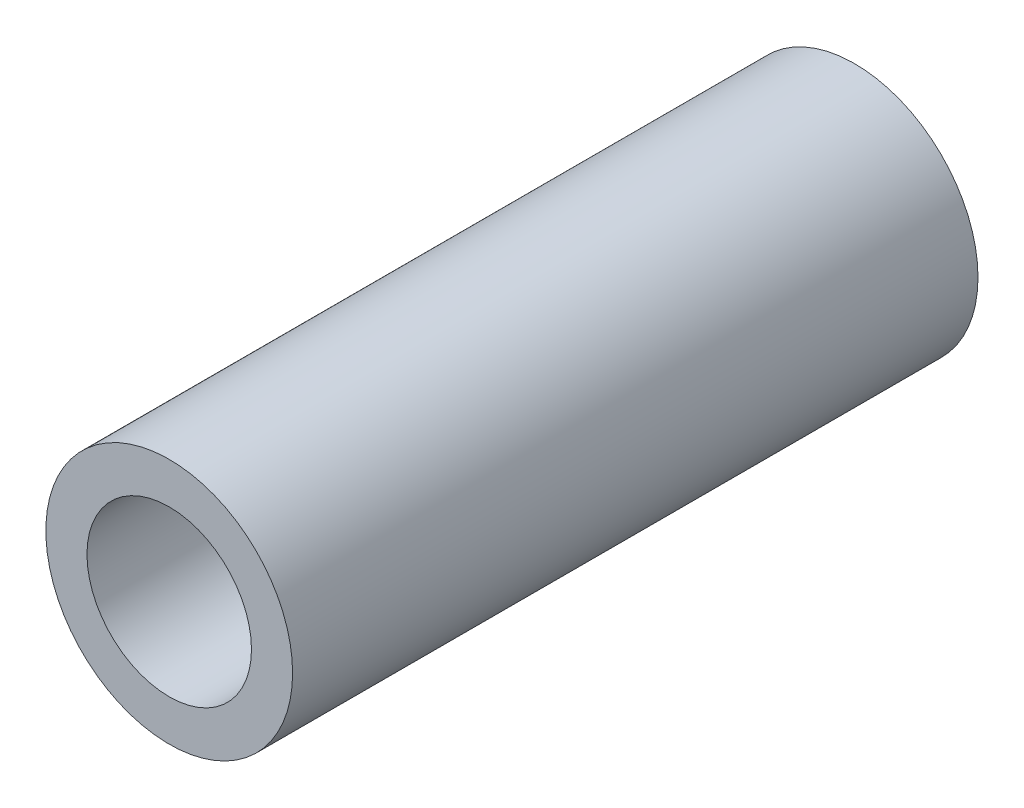
SolidWorks part; units mm, degrees
ref_plane "前视基准面" through (0, 0, 0) normal (0, 0, 1) x (1, 0, 0)
ref_plane "上视基准面" through (0, 0, 0) normal (0, 1, 0) x (1, 0, 0)
ref_plane "右视基准面" through (0, 0, 0) normal (1, 0, 0) x (0, 0, -1)
other "Configuration Table"
sketch "草图1" plane through (0, 0, 0) normal (0, 0, 1) x (1, 0, 0)
  circle A0 centre (0, 0) radius 9
  dimension "diameter" = 18
extrude "Sleeve" add sketch "草图1" along normal blind 50
sketch "草图2" plane through (0, 0, 50) normal (0, 0, 1) x (1, 0, 0)
  circle A0 centre (0, 0) radius 6
  dimension "diameter" = 12
extrude "Bore" cut sketch "草图2" against normal through all
